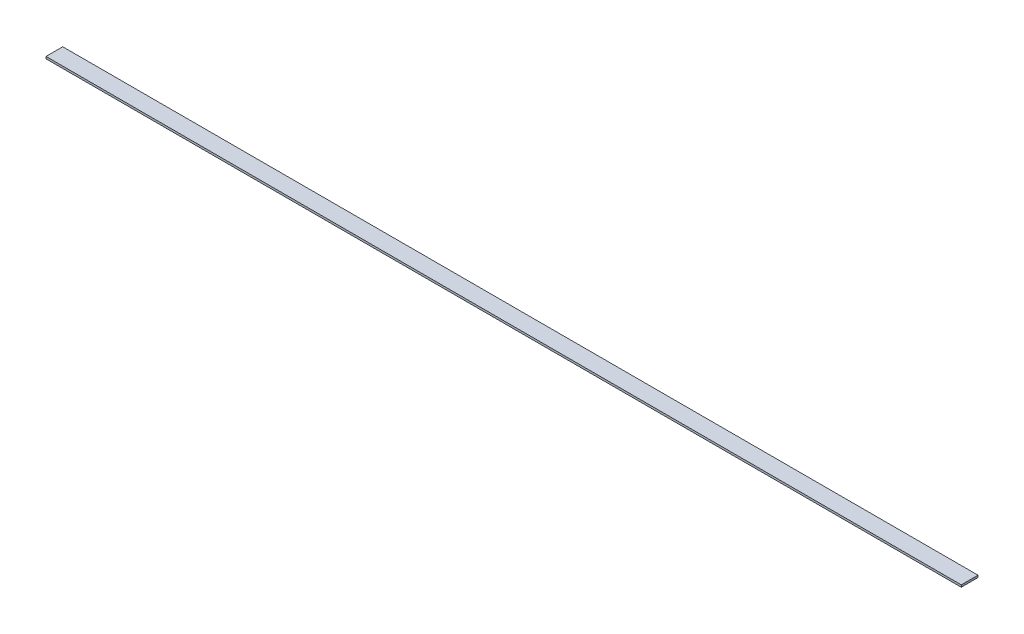
SolidWorks part; units mm, degrees
ref_plane "Front Plane" through (0, 0, 0) normal (0, 0, 1) x (1, 0, 0)
ref_plane "Top Plane" through (0, 0, 0) normal (0, 1, 0) x (1, 0, 0)
ref_plane "Right Plane" through (0, 0, 0) normal (1, 0, 0) x (0, 0, -1)
sketch "Sketch1" plane through (0, 0, 0) normal (0, 1, 0) x (1, 0, 0)
  line L1 (-546.5, 10) -> (546.5, 10)
  line L2 (-546.5, 10) -> (-546.5, -10)
  line L3 (-546.5, -10) -> (546.5, -10)
  line L4 (546.5, 10) -> (546.5, -10)
  line L5 (-546.5, 10) -> (546.5, -10) construction
  line L6 (-546.5, -10) -> (546.5, 10) construction
  point P0 (0, 0)
  dimension "D1" = 1093
  dimension "D2" = 20
extrude "Boss-Extrude1" add sketch "Sketch1" along normal blind 2.5
